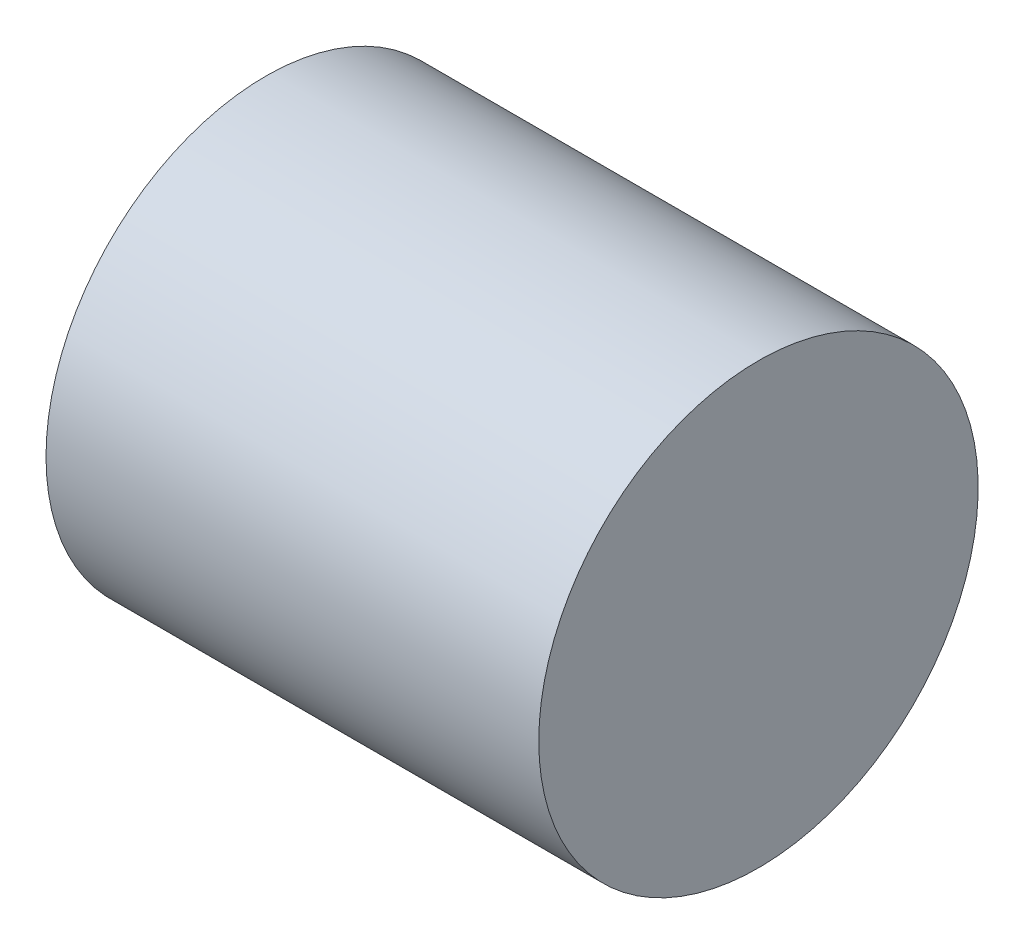
SolidWorks part; units mm, degrees
ref_plane "Front Plane" through (0, 0, 0) normal (0, 0, 1) x (1, 0, 0)
ref_plane "Top Plane" through (0, 0, 0) normal (0, 1, 0) x (1, 0, 0)
ref_plane "Right Plane" through (0, 0, 0) normal (1, 0, 0) x (0, 0, -1)
sketch "Sketch1" plane through (0, 0, 0) normal (0, 0, 1) x (1, 0, 0)
  line L0 (-22.7111, 0) -> (26.2631, 0) construction
  line L1 (0, 16.7643) -> (0, -12.0821) construction
  line L2 (0, 0) -> (0, 535)
  line L3 (0, 535) -> (-1200, 535)
  line L4 (-1200, 535) -> (-1200, 0)
  line L5 (-1200, 0) -> (0, 0)
  dimension "D1" = 535
  dimension "D2" = 1200
revolve "Revolve1" add sketch "Sketch1" angle 360 about L0
shell "Shell1" thickness 50
sketch "Sketch2" plane through (0, 0, 0) normal (1, 0, 0) x (0, 0, -1)
  circle A0 centre (0, 0) radius 535
  dimension "D1" = 1070
